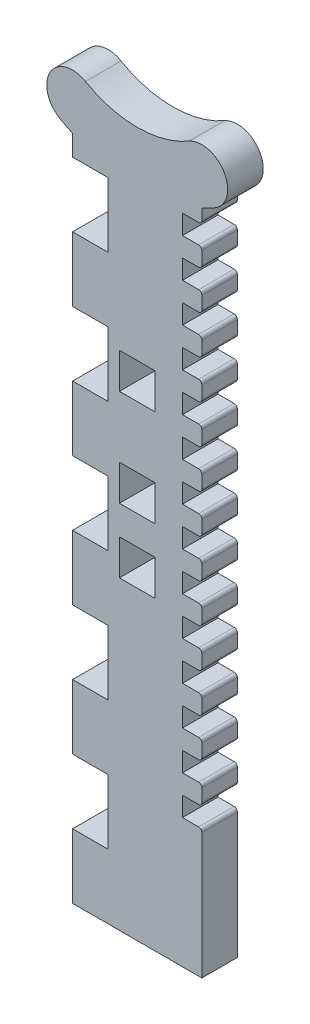
SolidWorks part; units mm, degrees
material "ﾁｰｸ材"
ref_plane "正面" through (0, 0, 0) normal (0, 0, 1) x (1, 0, 0)
ref_plane "平面" through (0, 0, 0) normal (0, 1, 0) x (1, 0, 0)
ref_plane "右側面" through (0, 0, 0) normal (1, 0, 0) x (0, 0, -1)
sketch "ｽｹｯﾁ1" plane through (0, 0, 0) normal (0, 0, 1) x (1, 0, 0)
  line L0 (-10, -21.8174) -> (-10, -125)
  line L1 (-10, -125) -> (10, -125)
  line L2 (10, -125) -> (10, -21.8174)
  arc A0 (-8, -13.8564) -> (8, -13.8564) centre (0, 0) ccw
  arc A1 (8, -13.8564) -> (12, -20.7846) centre (10, -17.3205) cw
  arc A2 (12, -20.7846) -> (10, -21.8174) centre (0, 0) cw
  arc A3 (-12, -20.7846) -> (-8, -13.8564) centre (-10, -17.3205) cw
  arc A4 (-10, -21.8174) -> (-12, -20.7846) centre (0, 0) cw
  point P9 (0, -125)
  dimension "D1" = 16
  dimension "D2" = 24
  dimension "D3" = 60
  dimension "D5" = 20
  dimension "D4" = 125
extrude "ﾎﾞｽ - 押し出し1" add sketch "ｽｹｯﾁ1" along normal blind 5.5
sketch "ｽｹｯﾁ2" plane through (0, 0, 5.5) normal (0, 0, 1) x (1, 0, 0)
  line L0 (-10, -95) -> (-10, -85)
  line L5 (-10, -95) -> (-4.5, -95)
  line L18 (-10, -21.8174) -> (-10, -125) construction
  line L59 (-10, -115) -> (-4.5, -115)
  line L60 (-10, -115) -> (-10, -105)
  line L61 (-10, -105) -> (-4.5, -105)
  line L62 (-4.5, -115) -> (-4.5, -105)
  line L63 (-10, -125) -> (10, -125) construction
  line L64 (-4.5, -95) -> (-4.5, -85)
  line L65 (-10, -85) -> (-4.5, -85)
  line L66 (-10, -75) -> (-10, -65)
  line L67 (-10, -75) -> (-4.5, -75)
  line L68 (-4.5, -75) -> (-4.5, -65)
  line L69 (-10, -65) -> (-4.5, -65)
  line L70 (-10, -55) -> (-10, -45)
  line L71 (-10, -55) -> (-4.5, -55)
  line L72 (-4.5, -55) -> (-4.5, -45)
  line L73 (-10, -45) -> (-4.5, -45)
  line L74 (-10, -35) -> (-10, -25)
  line L75 (-10, -35) -> (-4.5, -35)
  line L76 (-4.5, -35) -> (-4.5, -25)
  line L77 (-10, -25) -> (-4.5, -25)
  line L78 (0, 0) -> (0, -11.9682) construction
  line L99 (10, -125) -> (10, -21.8174) construction
  line L100 (10, -105) -> (7, -105)
  line L101 (10, -105) -> (10, -102)
  line L102 (10, -102) -> (7, -102)
  line L103 (7, -105) -> (7, -102)
  line L104 (10, -99) -> (10, -96)
  line L105 (10, -99) -> (7, -99)
  line L106 (7, -99) -> (7, -96)
  line L107 (10, -96) -> (7, -96)
  line L108 (10, -93) -> (10, -90)
  line L109 (10, -93) -> (7, -93)
  line L110 (7, -93) -> (7, -90)
  line L111 (10, -90) -> (7, -90)
  line L112 (10, -87) -> (10, -84)
  line L113 (10, -87) -> (7, -87)
  line L114 (7, -87) -> (7, -84)
  line L115 (10, -84) -> (7, -84)
  line L116 (10, -81) -> (10, -78)
  line L117 (10, -81) -> (7, -81)
  line L118 (7, -81) -> (7, -78)
  line L119 (10, -78) -> (7, -78)
  line L120 (10, -75) -> (10, -72)
  line L121 (10, -75) -> (7, -75)
  line L122 (7, -75) -> (7, -72)
  line L123 (10, -72) -> (7, -72)
  line L124 (10, -69) -> (10, -66)
  line L125 (10, -69) -> (7, -69)
  line L126 (7, -69) -> (7, -66)
  line L127 (10, -66) -> (7, -66)
  line L128 (10, -63) -> (10, -60)
  line L129 (10, -63) -> (7, -63)
  line L130 (7, -63) -> (7, -60)
  line L131 (10, -60) -> (7, -60)
  line L132 (10, -57) -> (10, -54)
  line L133 (10, -57) -> (7, -57)
  line L134 (7, -57) -> (7, -54)
  line L135 (10, -54) -> (7, -54)
  line L136 (10, -51) -> (10, -48)
  line L137 (10, -51) -> (7, -51)
  line L138 (7, -51) -> (7, -48)
  line L139 (10, -48) -> (7, -48)
  line L140 (10, -45) -> (10, -42)
  line L141 (10, -45) -> (7, -45)
  line L142 (7, -45) -> (7, -42)
  line L143 (10, -42) -> (7, -42)
  line L144 (10, -39) -> (10, -36)
  line L145 (10, -39) -> (7, -39)
  line L146 (7, -39) -> (7, -36)
  line L147 (10, -36) -> (7, -36)
  line L148 (10, -33) -> (10, -30)
  line L149 (10, -33) -> (7, -33)
  line L150 (7, -33) -> (7, -30)
  line L151 (10, -30) -> (7, -30)
  line L152 (10, -27) -> (10, -24)
  line L153 (10, -27) -> (7, -27)
  line L154 (7, -27) -> (7, -24)
  line L155 (10, -24) -> (7, -24)
  dimension "D1" = 5.5
  dimension "D2" = 10
  dimension "D3" = 10
  dimension "D5" = 3
  dimension "D4" = 5
  dimension "D6" = 3
  dimension "D7" = 20
  dimension "D8" = 14
extrude "ｶｯﾄ - 押し出し1" cut sketch "ｽｹｯﾁ2" against normal through all
sketch "ｽｹｯﾁ4" plane through (0, 0, 0) normal (0, 0, -1) x (-1, 0, 0)
  line L0 (0, 0) -> (0, -33.3742) construction
sketch "ｽｹｯﾁ5" plane through (0, 0, 5.5) normal (0, 0, 1) x (1, 0, 0)
  line L1 (-2.75, -62.25) -> (2.75, -62.25)
  line L2 (-2.75, -62.25) -> (-2.75, -67.75)
  line L3 (-2.75, -67.75) -> (2.75, -67.75)
  line L4 (2.75, -62.25) -> (2.75, -67.75)
  line L5 (-2.75, -62.25) -> (2.75, -67.75) construction
  line L6 (-2.75, -67.75) -> (2.75, -62.25) construction
  line L7 (-2.75, -47.25) -> (2.75, -47.25)
  line L8 (-2.75, -47.25) -> (-2.75, -52.75)
  line L9 (-2.75, -52.75) -> (2.75, -52.75)
  line L10 (2.75, -47.25) -> (2.75, -52.75)
  line L11 (-2.75, -47.25) -> (2.75, -52.75) construction
  line L12 (-2.75, -52.75) -> (2.75, -47.25) construction
  line L13 (-2.75, -72.25) -> (2.75, -72.25)
  line L14 (-2.75, -72.25) -> (-2.75, -77.75)
  line L15 (-2.75, -77.75) -> (2.75, -77.75)
  line L16 (2.75, -72.25) -> (2.75, -77.75)
  line L17 (-2.75, -72.25) -> (2.75, -77.75) construction
  line L18 (-2.75, -77.75) -> (2.75, -72.25) construction
  point P0 (0, -65)
  point P5 (0, -50)
  point P11 (0, -75)
  dimension "D1" = 5.5
  dimension "D2" = 5.5
  dimension "D3" = 65
  dimension "D4" = 5.5
  dimension "D5" = 5.5
  dimension "D6" = 50
  dimension "D7" = 5.5
  dimension "D8" = 5.5
  dimension "D9" = 75
extrude "ｶｯﾄ - 押し出し2" cut sketch "ｽｹｯﾁ5" against normal through all
fillet "ﾌｨﾚｯﾄ1" radius 0.5 28 edges at (10, -105, 2.75) (10, -102, 2.75) (10, -99, 2.75) (10, -96, 2.75) (10, -93, 2.75) (10, -90, 2.75) (10, -87, 2.75) (10, -84, 2.75) (10, -81, 2.75) (10, -78, 2.75) (10, -75, 2.75) (10, -72, 2.75) (10, -69, 2.75) (10, -66, 2.75) (10, -63, 2.75) (10, -60, 2.75) (10, -57, 2.75) (10, -54, 2.75) (10, -51, 2.75) (10, -48, 2.75) (10, -45, 2.75) (10, -42, 2.75) (10, -39, 2.75) (10, -36, 2.75) (10, -33, 2.75) (10, -30, 2.75) (10, -27, 2.75) (10, -24, 2.75)
